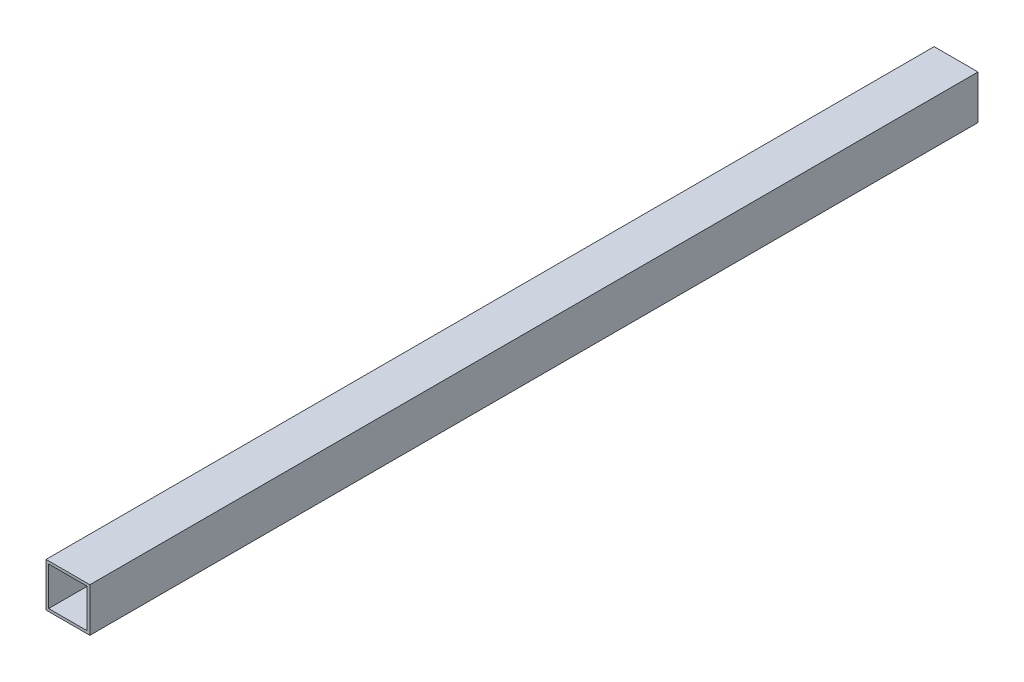
SolidWorks part; units mm, degrees
ref_plane "Front Plane" through (0, 0, 0) normal (0, 0, 1) x (1, 0, 0)
ref_plane "Top Plane" through (0, 0, 0) normal (0, 1, 0) x (1, 0, 0)
ref_plane "Right Plane" through (0, 0, 0) normal (1, 0, 0) x (0, 0, -1)
sketch "Sketch1" plane through (0, 0, 0) normal (0, 0, 1) x (1, 0, 0)
  line L1 (0, 0) -> (25.4, 0)
  line L2 (0, 0) -> (0, 25.4)
  line L3 (0, 25.4) -> (25.4, 25.4)
  line L4 (25.4, 0) -> (25.4, 25.4)
  dimension "D1" = 25.4
  dimension "D2" = 25.4
extrude "Extrude-Thin1" add sketch "Sketch1" along normal blind 514.35 thin thin type one direction reverse wall 1.524
